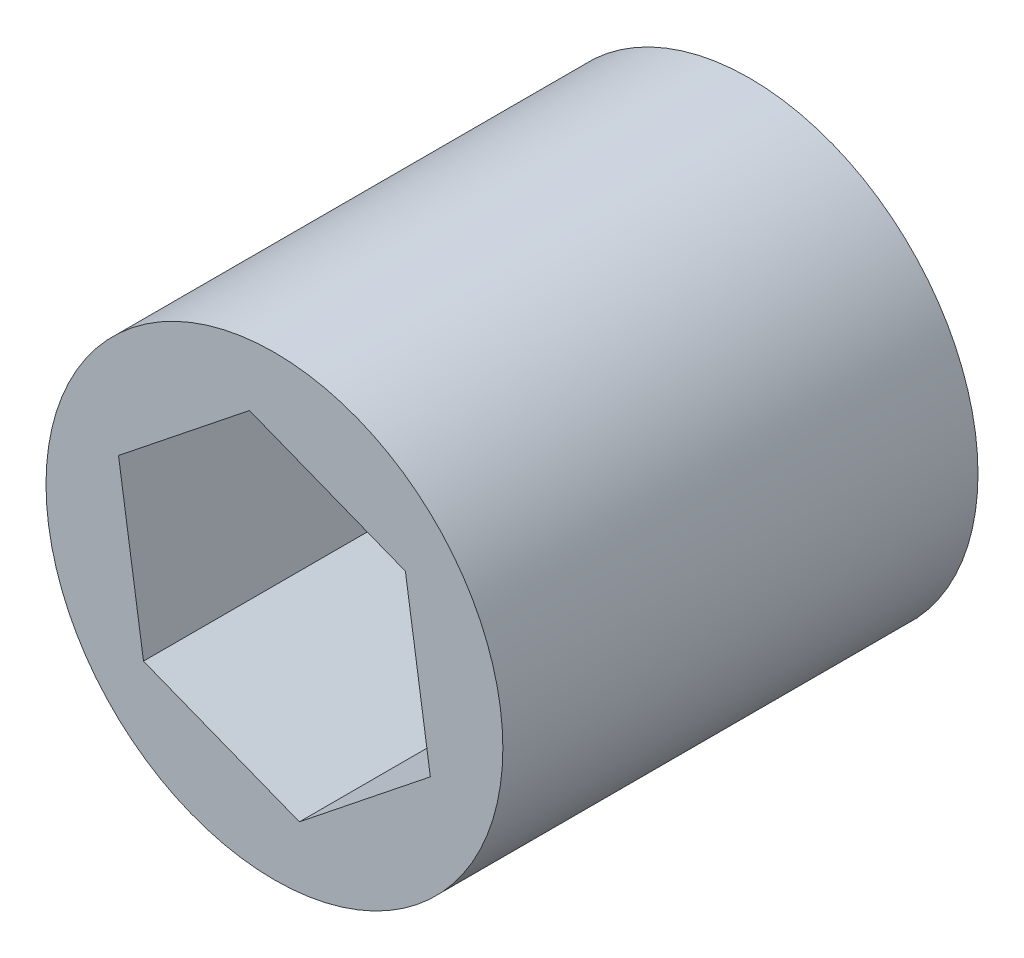
SolidWorks part; units mm, degrees
ref_plane "Front Plane" through (0, 0, 0) normal (0, 0, 1) x (1, 0, 0)
ref_plane "Top Plane" through (0, 0, 0) normal (0, 1, 0) x (1, 0, 0)
ref_plane "Right Plane" through (0, 0, 0) normal (1, 0, 0) x (0, 0, -1)
sketch "Sketch1" plane through (0, 0, 0) normal (0, 0, 1) x (1, 0, 0)
  line L1 (-6.8256, 2.6784) -> (-5.7324, -4.572)
  line L2 (-5.7324, -4.572) -> (1.0932, -7.2504)
  line L3 (1.0932, -7.2504) -> (6.8256, -2.6784)
  line L4 (6.8256, -2.6784) -> (5.7324, 4.572)
  line L5 (5.7324, 4.572) -> (-1.0932, 7.2504)
  line L6 (-1.0932, 7.2504) -> (-6.8256, 2.6784)
  circle A0 centre (0, 0) radius 10
  circle A1 centre (0, 0) radius 6.35 construction
  dimension "D1" = 12.7
  dimension "D2" = 20
extrude "Boss-Extrude1" add sketch "Sketch1" along normal blind 20.8
